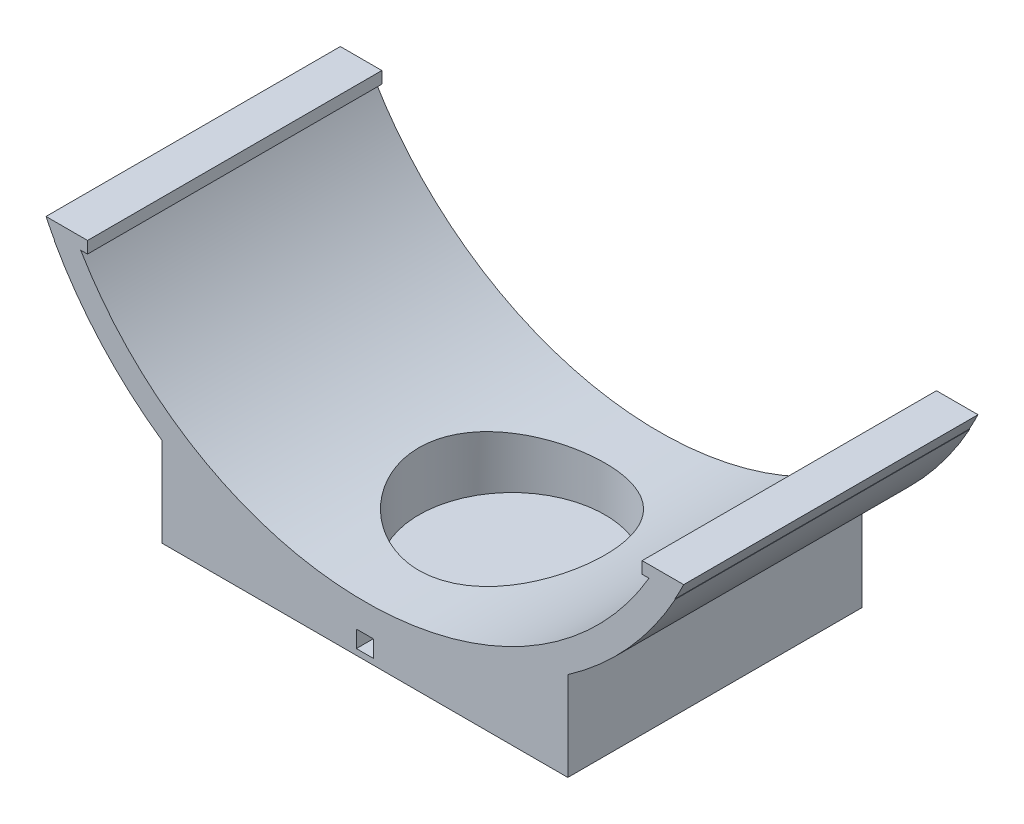
SolidWorks part; units mm, degrees
ref_plane "前视基准面" through (0, 0, 0) normal (0, 0, 1) x (1, 0, 0)
ref_plane "上视基准面" through (0, 0, 0) normal (0, 1, 0) x (1, 0, 0)
ref_plane "右视基准面" through (0, 0, 0) normal (1, 0, 0) x (0, 0, -1)
sketch "草图1" plane through (0, 0, 0) normal (0, 0, 1) x (1, 0, 0)
  arc A0 (-203, 0) -> (203, 0) centre (0, 0) ccw
  arc A1 (-210, 0) -> (210, 0) centre (0, 0) ccw
  arc A2 (-203, 0) -> (203, 0) centre (0, 0) ccw
  circle A3 centre (0, 0) radius 210
  circle A4 centre (0, 0) radius 203
  point P12 (0, 0)
extrude "凸台-拉伸2" add sketch "草图1" along normal blind 174
sketch "草图2" plane through (0, 0, 174) normal (0, 0, 1) x (1, 0, 0)
  line L0 (-173.7354, -102) -> (-170.7354, -102)
  line L1 (-170.7354, -102) -> (-170.7354, -105)
  line L2 (-170.7354, -105) -> (-173.7354, -105)
  line L3 (173.7354, -102) -> (170.7354, -102)
  line L4 (-173.7354, -102) -> (-175.5135, -102)
  line L6 (173.7354, -102) -> (175.5135, -102)
  line L7 (173.7354, -105) -> (170.7354, -105)
  line L8 (170.7354, -105) -> (170.7354, -102)
  circle A0 centre (0, 0) radius 203 construction
  arc A1 (0, -203) -> (-173.7354, -105) centre (0, 0) ccw
  circle M4 centre (0, 0) radius 203
extrude "凸台-拉伸4" add sketch "草图2" against normal up to surface (174 mm away) contours L0 L4 L2 L1 M4 | L8 L7 L6 L3 M4 up to face at (203, 0, 0)
sketch "草图3" plane through (0, 0, 174) normal (0, 0, 1) x (1, 0, 0)
  line L0 (-170.7354, -102) -> (238.3336, -102)
  line L1 (238.3336, -102) -> (254.3342, 272.2925)
  line L2 (254.3342, 272.2925) -> (-334.5694, 221.8511)
  line L3 (-170.7354, -102) -> (-306.8306, -102)
  line L4 (-306.8306, -102) -> (-334.5694, 221.8511)
extrude "切除-拉伸1" cut sketch "草图3" against normal blind 654
ref_plane "基准面1" through (0, -209.75, 0) normal (0, 1, 0) x (1, 0, 0)
sketch "草图5" plane through (0, 0, 174) normal (0, 0, 1) x (1, 0, 0)
  line L0 (0, -209.75) -> (120, -209.75)
  line L1 (95.7, -209.75) -> (-95.7, -209.75) construction
  line L2 (120, -209.75) -> (120, -172.0322)
  line L3 (0, -209.75) -> (-120, -209.75)
  line L4 (-120, -209.75) -> (-120, -172.0322)
  arc A0 (-120, -172.0322) -> (120, -172.0322) centre (0, 0) ccw
  arc M3 (-183.5647, -102) -> (183.5647, -102) centre (0, 0) ccw
extrude "凸台-拉伸5" add sketch "草图5" against normal up to surface (174 mm away) contours L4 L3 M3 | L0 L2 M3 up to face at (0, -129.25, 0)
sketch "草图6" plane through (0, 0, 174) normal (0, 0, 1) x (1, 0, 0)
  line L0 (-175.5135, -102) -> (-166.1957, -102)
  line L1 (175.5135, -102) -> (166.1957, -102)
  arc A0 (-166.1957, -102) -> (166.1957, -102) centre (0, 0) ccw
  arc A1 (-175.5135, -102) -> (175.5135, -102) centre (0, 0) ccw
extrude "凸台-拉伸6" add sketch "草图6" against normal up to surface (174 mm away) up to face at (0, -151.228, 0)
sketch "草图7" plane through (0, 0, 174) normal (0, 0, 1) x (1, 0, 0)
  line L0 (-166.9331, -92) -> (-166.9331, -95)
  line L1 (171.9331, -92) -> (166.9331, -92)
  line L2 (-171.9331, -92) -> (-166.9331, -92)
  line L3 (-188.4969, -92) -> (-171.9331, -92)
  line L4 (171.9331, -92) -> (188.4969, -92)
  line L5 (-166.9331, -95) -> (-170.2939, -95)
  line L6 (166.9331, -92) -> (166.9331, -95)
  line L7 (166.9331, -95) -> (170.2939, -95)
  arc A1 (-188.4969, -92) -> (188.4969, -92) centre (0, 0) ccw
  arc A2 (-170.2939, -95) -> (170.2939, -95) centre (0, 0) ccw
extrude "凸台-拉伸7" add sketch "草图7" against normal up to surface (174 mm away) up to face at (0, -169.2192, 0)
sketch "草图8" plane through (0, 0, 0) normal (0, 0, -1) x (-1, 0, 0)
  line L0 (166.9331, -92) -> (163.9331, -92)
  line L1 (163.9331, -92) -> (163.9331, -99)
  line L2 (163.9331, -99) -> (168, -99)
  line L3 (166.9331, -92) -> (166.9331, -95)
  line L4 (166.9331, -95) -> (170.2939, -95)
  line L6 (-166.9331, -95) -> (-170.2939, -95)
  line L7 (-166.9331, -92) -> (-166.9331, -95)
  line L8 (-163.9331, -99) -> (-168, -99)
  line L9 (-163.9331, -92) -> (-163.9331, -99)
  line L10 (-166.9331, -92) -> (-163.9331, -92)
  arc A0 (-170.2939, -95) -> (170.2939, -95) centre (0, 0) ccw construction
  arc A1 (168, -99) -> (170.2939, -95) centre (0, 0) ccw
  arc A2 (-168, -99) -> (-170.2939, -95) centre (0, 0) cw
extrude "凸台-拉伸8" add sketch "草图8" against normal up to surface (174 mm away) up to face at (0, -135.959, 174)
sketch "草图9" plane through (0, 0, 174) normal (0, 0, 1) x (1, 0, 0)
  line L0 (0, -195) -> (0, -225)
  line L1 (0, -225) -> (120, -225)
  line L2 (120, -225) -> (120, -209.75)
  line L3 (120, -209.75) -> (-120, -209.75)
  line L4 (-120, -209.75) -> (-120, -225)
  line L5 (-120, -225) -> (18.0074, -225)
  arc A2 (-168, -99) -> (168, -99) centre (0, 0) ccw construction
  line M11 (-120, -209.75) -> (-10.2439, -209.75)
  arc M12 (-10.2439, -209.75) -> (10.2439, -209.75) centre (0, 0) ccw
  line M13 (10.2439, -209.75) -> (120, -209.75)
extrude "凸台-拉伸9" add sketch "草图9" against normal up to vertex (174 mm away) contours L1 L2 L0 M13 M12 | L4 L5 L0 M12 M11 up to point (120, -209.75, 0)
sketch "草图10" plane through (0, 0, 174) normal (0, 0, 1) x (1, 0, 0)
  line L0 (-5, -221.5) -> (-5, -211.5)
  line L2 (0, -211.5) -> (5, -211.5)
  line L3 (-55, -195) -> (-55, -221.5)
  line L4 (-5, -211.5) -> (0, -211.5)
  line L8 (5, -211.5) -> (5, -221.5)
  line L9 (5, -221.5) -> (-5, -221.5)
sketch "草图11" plane through (0, 0, 0) normal (0, 1, 0) x (1, 0, 0)
  line L0 (-163.9331, -87) -> (188.4969, -87)
  line L1 (-163.9331, -174) -> (-163.9331, 0) construction
  line L2 (188.4969, 0) -> (188.4969, -174) construction
  line L3 (0, 0) -> (0, -137.3076)
  circle A0 centre (0, -87) radius 55
extrude "切除-拉伸4" cut sketch "草图11" against normal up to vertex (221.5 mm away) up to point (-55, -221.5, 174)
extrude "切除-拉伸5" cut sketch "草图10" against normal blind 87 contours L9 L8 L2 L4 L0
